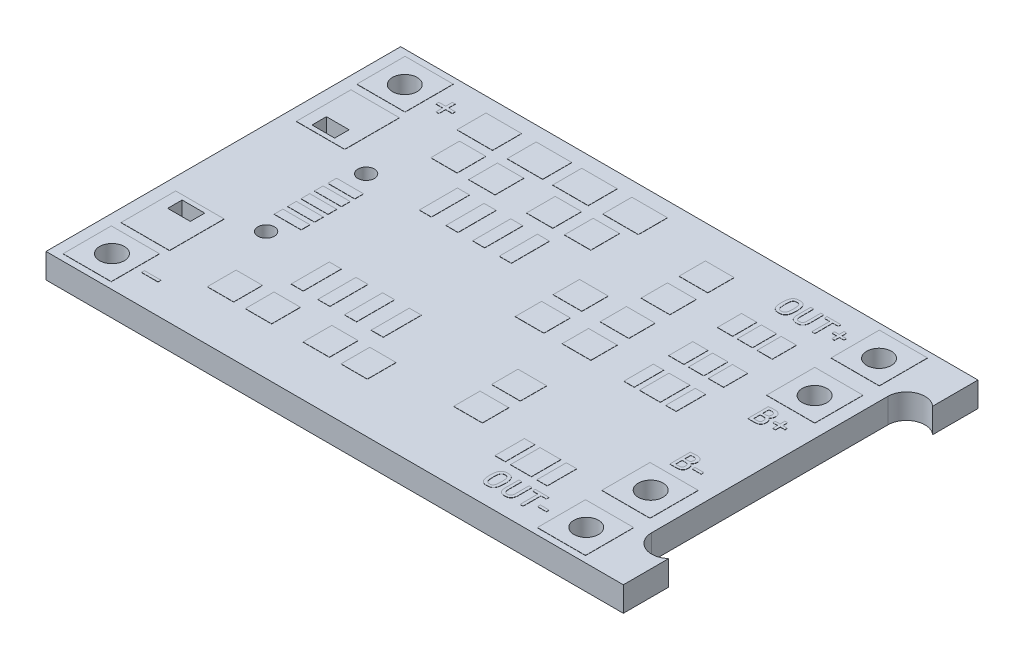
SolidWorks part; units mm, degrees
ref_plane "Front" through (0, 0, 0) normal (0, 0, 1) x (1, 0, 0)
ref_plane "Top" through (0, 0, 0) normal (0, 1, 0) x (1, 0, 0)
ref_plane "Right" through (0, 0, 0) normal (1, 0, 0) x (0, 0, -1)
sketch "Sketch1" plane through (0, 0, 0) normal (0, 1, 0) x (1, 0, 0)
  line L0 (0.5204, 8.2926) -> (0.5204, 5.9545) construction
  line L1 (0.5204, 5.9545) -> (2.8585, 5.9545) construction
  line L2 (2.8585, 5.9545) -> (2.8585, 8.2926) construction
  line L3 (2.8585, 8.2926) -> (0.5204, 8.2926) construction
  line L4 (23.5204, 8.2926) -> (23.5204, 5.9545) construction
  line L5 (23.5204, 5.9545) -> (25.8585, 5.9545) construction
  line L6 (25.8585, 5.9545) -> (25.8585, 8.2926) construction
  line L7 (25.8585, 8.2926) -> (23.5204, 8.2926) construction
  line L8 (0.5204, -8.2926) -> (0.5204, -5.9545) construction
  line L9 (0.5204, -5.9545) -> (2.8585, -5.9545) construction
  line L10 (2.8585, -5.9545) -> (2.8585, -8.2926) construction
  line L11 (2.8585, -8.2926) -> (0.5204, -8.2926) construction
  line L12 (23.5204, -8.2926) -> (23.5204, -5.9545) construction
  line L13 (23.5204, -5.9545) -> (25.8585, -5.9545) construction
  line L14 (25.8585, -5.9545) -> (25.8585, -8.2926) construction
  line L15 (25.8585, -8.2926) -> (23.5204, -8.2926) construction
  line L16 (23.5204, 5.165) -> (23.5204, 2.827) construction
  line L17 (23.5204, 2.827) -> (25.8585, 2.827) construction
  line L18 (25.8585, 2.827) -> (25.8585, 5.165) construction
  line L19 (25.8585, 5.165) -> (23.5204, 5.165) construction
  line L20 (23.5204, -5.165) -> (23.5204, -2.827) construction
  line L21 (23.5204, -2.827) -> (25.8585, -2.827) construction
  line L22 (25.8585, -2.827) -> (25.8585, -5.165) construction
  line L23 (25.8585, -5.165) -> (23.5204, -5.165) construction
  line L24 (26.5, 5.7292) -> (26.5, -5.7292)
  line L25 (4.865, 7.8748) -> (4.865, 6.4662) construction
  line L26 (4.865, 6.4662) -> (6.5892, 6.4662) construction
  line L27 (6.5892, 6.4662) -> (6.5892, 7.8748) construction
  line L28 (6.5892, 7.8748) -> (4.865, 7.8748) construction
  line L29 (7.2974, 7.8748) -> (7.2974, 6.4662) construction
  line L30 (7.2974, 6.4662) -> (9.0216, 6.4662) construction
  line L31 (9.0216, 6.4662) -> (9.0216, 7.8748) construction
  line L32 (9.0216, 7.8748) -> (7.2974, 7.8748) construction
  line L33 (9.5065, 7.8748) -> (9.5065, 6.4662) construction
  line L34 (9.5065, 6.4662) -> (11.2307, 6.4662) construction
  line L35 (11.2307, 6.4662) -> (11.2307, 7.8748) construction
  line L36 (11.2307, 7.8748) -> (9.5065, 7.8748) construction
  line L37 (11.9389, 7.8748) -> (11.9389, 6.4662) construction
  line L38 (11.9389, 6.4662) -> (13.6631, 6.4662) construction
  line L39 (13.6631, 6.4662) -> (13.6631, 7.8748) construction
  line L40 (13.6631, 7.8748) -> (11.9389, 7.8748) construction
  line L41 (5.4038, 6.0505) -> (5.4038, 4.6573) construction
  line L42 (5.4038, 4.6573) -> (6.6816, 4.6573) construction
  line L43 (6.6816, 4.6573) -> (6.6816, 6.0505) construction
  line L44 (6.6816, 6.0505) -> (5.4038, 6.0505) construction
  line L45 (7.2435, 6.0505) -> (7.2435, 4.6573) construction
  line L46 (7.2435, 4.6573) -> (8.5212, 4.6573) construction
  line L47 (8.5212, 4.6573) -> (8.5212, 6.0505) construction
  line L48 (8.5212, 6.0505) -> (7.2435, 6.0505) construction
  line L49 (10.0453, 6.0505) -> (10.0453, 4.6573) construction
  line L50 (10.0453, 4.6573) -> (11.3231, 4.6573) construction
  line L51 (11.3231, 4.6573) -> (11.3231, 6.0505) construction
  line L52 (11.3231, 6.0505) -> (10.0453, 6.0505) construction
  line L53 (11.885, 6.0505) -> (11.885, 4.6573) construction
  line L54 (11.885, 4.6573) -> (13.1627, 4.6573) construction
  line L55 (13.1627, 4.6573) -> (13.1627, 6.0505) construction
  line L56 (13.1627, 6.0505) -> (11.885, 6.0505) construction
  line L57 (5.4038, -4.7844) -> (5.4038, -6.1777) construction
  line L58 (5.4038, -6.1777) -> (6.6816, -6.1777) construction
  line L59 (6.6816, -6.1777) -> (6.6816, -4.7844) construction
  line L60 (6.6816, -4.7844) -> (5.4038, -4.7844) construction
  line L61 (7.2435, -4.7844) -> (7.2435, -6.1777) construction
  line L62 (7.2435, -6.1777) -> (8.5212, -6.1777) construction
  line L63 (8.5212, -6.1777) -> (8.5212, -4.7844) construction
  line L64 (8.5212, -4.7844) -> (7.2435, -4.7844) construction
  line L65 (10.0453, -4.7844) -> (10.0453, -6.1777) construction
  line L66 (10.0453, -6.1777) -> (11.3231, -6.1777) construction
  line L67 (11.3231, -6.1777) -> (11.3231, -4.7844) construction
  line L68 (11.3231, -4.7844) -> (10.0453, -4.7844) construction
  line L69 (11.885, -4.7844) -> (11.885, -6.1777) construction
  line L70 (11.885, -6.1777) -> (13.1627, -6.1777) construction
  line L71 (13.1627, -6.1777) -> (13.1627, -4.7844) construction
  line L72 (13.1627, -4.7844) -> (11.885, -4.7844) construction
  line L73 (0.6154, 5.5743) -> (0.6154, 2.9246) construction
  line L74 (0.6154, 2.9246) -> (2.9644, 2.9246) construction
  line L75 (2.9644, 2.9246) -> (2.9644, 5.5743) construction
  line L76 (2.9644, 5.5743) -> (0.6154, 5.5743) construction
  line L77 (0.6154, -5.5743) -> (0.6154, -2.9246) construction
  line L78 (0.6154, -2.9246) -> (2.9644, -2.9246) construction
  line L79 (2.9644, -2.9246) -> (2.9644, -5.5743) construction
  line L80 (2.9644, -5.5743) -> (0.6154, -5.5743) construction
  line L81 (17.7933, 6.9801) -> (16.4001, 6.9801) construction
  line L82 (16.4001, 6.9801) -> (16.4001, 5.7023) construction
  line L83 (16.4001, 5.7023) -> (17.7933, 5.7023) construction
  line L84 (17.7933, 5.7023) -> (17.7933, 6.9801) construction
  line L85 (17.7933, 5.1404) -> (16.4001, 5.1404) construction
  line L86 (16.4001, 5.1404) -> (16.4001, 3.8627) construction
  line L87 (16.4001, 3.8627) -> (17.7933, 3.8627) construction
  line L88 (17.7933, 3.8627) -> (17.7933, 5.1404) construction
  line L89 (17.7933, 3.1511) -> (16.4001, 3.1511) construction
  line L90 (16.4001, 3.1511) -> (16.4001, 1.8734) construction
  line L91 (16.4001, 1.8734) -> (17.7933, 1.8734) construction
  line L92 (17.7933, 1.8734) -> (17.7933, 3.1511) construction
  line L93 (17.7933, 1.3115) -> (16.4001, 1.3115) construction
  line L94 (16.4001, 1.3115) -> (16.4001, 0.0337) construction
  line L95 (16.4001, 0.0337) -> (17.7933, 0.0337) construction
  line L96 (17.7933, 0.0337) -> (17.7933, 1.3115) construction
  line L97 (17.7933, -2.1107) -> (16.4001, -2.1107) construction
  line L98 (16.4001, -2.1107) -> (16.4001, -3.3885) construction
  line L99 (16.4001, -3.3885) -> (17.7933, -3.3885) construction
  line L100 (17.7933, -3.3885) -> (17.7933, -2.1107) construction
  line L101 (17.7933, -3.9504) -> (16.4001, -3.9504) construction
  line L102 (16.4001, -3.9504) -> (16.4001, -5.2281) construction
  line L103 (16.4001, -5.2281) -> (17.7933, -5.2281) construction
  line L104 (17.7933, -5.2281) -> (17.7933, -3.9504) construction
  line L105 (15.5148, 3.1511) -> (14.1215, 3.1511) construction
  line L106 (14.1215, 3.1511) -> (14.1215, 1.8734) construction
  line L107 (14.1215, 1.8734) -> (15.5148, 1.8734) construction
  line L108 (15.5148, 1.8734) -> (15.5148, 3.1511) construction
  line L109 (15.5148, 1.3115) -> (14.1215, 1.3115) construction
  line L110 (14.1215, 1.3115) -> (14.1215, 0.0337) construction
  line L111 (14.1215, 0.0337) -> (15.5148, 0.0337) construction
  line L112 (15.5148, 0.0337) -> (15.5148, 1.3115) construction
  line L113 (19.4816, 5.6505) -> (19.4816, 4.4805) construction
  line L114 (19.4816, 4.4805) -> (20.2205, 4.4805) construction
  line L115 (20.2205, 4.4805) -> (20.2205, 5.6505) construction
  line L116 (20.2205, 5.6505) -> (19.4816, 5.6505) construction
  line L117 (20.4438, 5.6505) -> (20.4438, 4.4805) construction
  line L118 (20.4438, 4.4805) -> (21.1827, 4.4805) construction
  line L119 (21.1827, 4.4805) -> (21.1827, 5.6505) construction
  line L120 (21.1827, 5.6505) -> (20.4438, 5.6505) construction
  line L121 (21.4059, 5.6505) -> (21.4059, 4.4805) construction
  line L122 (21.4059, 4.4805) -> (22.1449, 4.4805) construction
  line L123 (22.1449, 4.4805) -> (22.1449, 5.6505) construction
  line L124 (22.1449, 5.6505) -> (21.4059, 5.6505) construction
  line L125 (19.4816, 3.2874) -> (19.4816, 2.1174) construction
  line L126 (19.4816, 2.1174) -> (20.2205, 2.1174) construction
  line L127 (20.2205, 2.1174) -> (20.2205, 3.2874) construction
  line L128 (20.2205, 3.2874) -> (19.4816, 3.2874) construction
  line L129 (20.4438, 3.2874) -> (20.4438, 2.1174) construction
  line L130 (20.4438, 2.1174) -> (21.1827, 2.1174) construction
  line L131 (21.1827, 2.1174) -> (21.1827, 3.2874) construction
  line L132 (21.1827, 3.2874) -> (20.4438, 3.2874) construction
  line L133 (21.4059, 3.2874) -> (21.4059, 2.1174) construction
  line L134 (21.4059, 2.1174) -> (22.1449, 2.1174) construction
  line L135 (22.1449, 2.1174) -> (22.1449, 3.2874) construction
  line L136 (22.1449, 3.2874) -> (21.4059, 3.2874) construction
  line L137 (5.2898, 1.0876) -> (5.2898, 1.5124) construction
  line L138 (5.2898, 1.5124) -> (3.9782, 1.5124) construction
  line L139 (3.9782, 1.5124) -> (3.9782, 1.0876) construction
  line L140 (3.9782, 1.0876) -> (5.2898, 1.0876) construction
  line L141 (5.2898, 0.4376) -> (5.2898, 0.8624) construction
  line L142 (5.2898, 0.8624) -> (3.9782, 0.8624) construction
  line L143 (3.9782, 0.8624) -> (3.9782, 0.4376) construction
  line L144 (3.9782, 0.4376) -> (5.2898, 0.4376) construction
  line L145 (5.2898, -0.2124) -> (5.2898, 0.2124) construction
  line L146 (5.2898, 0.2124) -> (3.9782, 0.2124) construction
  line L147 (3.9782, 0.2124) -> (3.9782, -0.2124) construction
  line L148 (3.9782, -0.2124) -> (5.2898, -0.2124) construction
  line L149 (5.2898, -0.8624) -> (5.2898, -0.4376) construction
  line L150 (5.2898, -0.4376) -> (3.9782, -0.4376) construction
  line L151 (3.9782, -0.4376) -> (3.9782, -0.8624) construction
  line L152 (3.9782, -0.8624) -> (5.2898, -0.8624) construction
  line L153 (5.2898, -1.5124) -> (5.2898, -1.0876) construction
  line L154 (5.2898, -1.0876) -> (3.9782, -1.0876) construction
  line L155 (3.9782, -1.0876) -> (3.9782, -1.5124) construction
  line L156 (3.9782, -1.5124) -> (5.2898, -1.5124) construction
  line L157 (11.787, 4.0316) -> (11.787, 2.1824) construction
  line L158 (11.787, 2.1824) -> (11.2007, 2.1824) construction
  line L159 (11.2007, 2.1824) -> (11.2007, 4.0316) construction
  line L160 (11.2007, 4.0316) -> (11.787, 4.0316) construction
  line L161 (10.4941, 4.0316) -> (10.4941, 2.1824) construction
  line L162 (10.4941, 2.1824) -> (9.9077, 2.1824) construction
  line L163 (9.9077, 2.1824) -> (9.9077, 4.0316) construction
  line L164 (9.9077, 4.0316) -> (10.4941, 4.0316) construction
  line L165 (9.2011, 4.0316) -> (9.2011, 2.1824) construction
  line L166 (9.2011, 2.1824) -> (8.6148, 2.1824) construction
  line L167 (8.6148, 2.1824) -> (8.6148, 4.0316) construction
  line L168 (8.6148, 4.0316) -> (9.2011, 4.0316) construction
  line L169 (7.9082, 4.0316) -> (7.9082, 2.1824) construction
  line L170 (7.9082, 2.1824) -> (7.3219, 2.1824) construction
  line L171 (7.3219, 2.1824) -> (7.3219, 4.0316) construction
  line L172 (7.3219, 4.0316) -> (7.9082, 4.0316) construction
  line L173 (7.9082, -4.0316) -> (7.9082, -2.1824) construction
  line L174 (7.9082, -2.1824) -> (7.3219, -2.1824) construction
  line L175 (7.3219, -2.1824) -> (7.3219, -4.0316) construction
  line L176 (7.3219, -4.0316) -> (7.9082, -4.0316) construction
  line L177 (9.2011, -4.0316) -> (9.2011, -2.1824) construction
  line L178 (9.2011, -2.1824) -> (8.6148, -2.1824) construction
  line L179 (8.6148, -2.1824) -> (8.6148, -4.0316) construction
  line L180 (8.6148, -4.0316) -> (9.2011, -4.0316) construction
  line L181 (10.4941, -4.0316) -> (10.4941, -2.1824) construction
  line L182 (10.4941, -2.1824) -> (9.9077, -2.1824) construction
  line L183 (9.9077, -2.1824) -> (9.9077, -4.0316) construction
  line L184 (9.9077, -4.0316) -> (10.4941, -4.0316) construction
  line L185 (11.787, -4.0316) -> (11.787, -2.1824) construction
  line L186 (11.787, -2.1824) -> (11.2007, -2.1824) construction
  line L187 (11.2007, -2.1824) -> (11.2007, -4.0316) construction
  line L188 (11.2007, -4.0316) -> (11.787, -4.0316) construction
  line L189 (19.47, 1.3863) -> (19.47, -0.0449) construction
  line L190 (19.47, -0.0449) -> (19.9752, -0.0449) construction
  line L191 (19.9752, -0.0449) -> (19.9752, 1.3863) construction
  line L192 (19.9752, 1.3863) -> (19.47, 1.3863) construction
  line L193 (21.5026, 1.3863) -> (21.5026, -0.0449) construction
  line L194 (21.5026, -0.0449) -> (22.0078, -0.0449) construction
  line L195 (22.0078, -0.0449) -> (22.0078, 1.3863) construction
  line L196 (22.0078, 1.3863) -> (21.5026, 1.3863) construction
  line L197 (20.2278, 1.3863) -> (20.2278, -0.0449) construction
  line L198 (20.2278, -0.0449) -> (21.238, -0.0449) construction
  line L199 (21.238, -0.0449) -> (21.238, 1.3863) construction
  line L200 (21.238, 1.3863) -> (20.2278, 1.3863) construction
  line L201 (19.47, -4.8678) -> (19.47, -6.299) construction
  line L202 (19.47, -6.299) -> (19.9752, -6.299) construction
  line L203 (19.9752, -6.299) -> (19.9752, -4.8678) construction
  line L204 (19.9752, -4.8678) -> (19.47, -4.8678) construction
  line L205 (20.2278, -4.8678) -> (20.2278, -6.299) construction
  line L206 (20.2278, -6.299) -> (21.238, -6.299) construction
  line L207 (21.238, -6.299) -> (21.238, -4.8678) construction
  line L208 (21.238, -4.8678) -> (20.2278, -4.8678) construction
  line L209 (21.5026, -4.8678) -> (21.5026, -6.299) construction
  line L210 (21.5026, -6.299) -> (22.0078, -6.299) construction
  line L211 (22.0078, -6.299) -> (22.0078, -4.8678) construction
  line L212 (22.0078, -4.8678) -> (21.5026, -4.8678) construction
  line L213 (28, 8.6) -> (0, 8.6)
  line L214 (0, 8.6) -> (0, -8.6)
  line L215 (0, -8.6) -> (28, -8.6)
  line L216 (28, -8.6) -> (28, -6.4)
  line L217 (28, 6.4) -> (28, 8.6)
  line L218 (0, 0) -> (26.5, 0) construction
  line L219 (2.25, -3.15) -> (2.25, -3.85)
  line L220 (1.15, 3.15) -> (2.25, 3.15)
  line L221 (1.15, 3.15) -> (1.15, 3.85)
  line L222 (1.15, 3.85) -> (2.25, 3.85)
  line L223 (2.25, 3.15) -> (2.25, 3.85)
  line L224 (1.15, -3.85) -> (2.25, -3.85)
  line L225 (1.15, -3.15) -> (1.15, -3.85)
  line L226 (1.15, -3.15) -> (2.25, -3.15)
  circle A0 centre (24.7, 7.1) radius 0.6
  circle A1 centre (1.7, 7.1) radius 0.6
  circle A2 centre (24.7, -7.1) radius 0.6
  circle A3 centre (1.7, -7.1) radius 0.6
  circle A4 centre (24.7, 3.9747) radius 0.6
  circle A5 centre (24.7, -3.975) radius 0.6
  arc A6 (28, 6.4) -> (26.5, 5.7292) centre (27.4, 5.7292) ccw
  arc A7 (26.5, -5.7292) -> (28, -6.4) centre (27.4, -5.7292) ccw
  circle A8 centre (4.5, 2.425) radius 0.4
  circle A9 centre (4.5, -2.425) radius 0.4
  point P245 (1.7, 3.15)
  dimension "D5" = 0.9
  dimension "D6" = 1.2
  dimension "D8" = 23
  dimension "D10" = 14.2
  dimension "D11" = 3.125
  dimension "D12" = 3.1253
  dimension "D13" = 0.8
  dimension "D1" = 28
  dimension "D2" = 17.1999
  dimension "D3" = 1.5
  dimension "D4" = 12.8
  dimension "D7" = 1.7
  dimension "D9" = 1.5
  dimension "D14" = 2.425
  dimension "D15" = 4.5
  dimension "D16" = 1.1
  dimension "D17" = 0.7
  dimension "D18" = 3.15
extrude "PCB" add sketch "Sketch1" along normal blind 1.2
sketch "Sketch2" plane through (0, 1.2, 0) normal (0, 1, 0) x (1, 0, 0)
  line L0 (3.6016, 7.1809) -> (3.6016, 7.5098)
  line L1 (0.5204, 8.2926) -> (2.8585, 8.2926)
  line L2 (0.5204, 8.2926) -> (0.5204, 5.9545)
  line L3 (0.5204, 5.9545) -> (2.8585, 5.9545)
  line L4 (2.8585, 8.2926) -> (2.8585, 5.9545)
  line L5 (0.6154, 5.5743) -> (2.9644, 5.5743)
  line L6 (0.6154, 5.5743) -> (0.6154, 2.9246)
  line L7 (0.6154, 2.9246) -> (2.9644, 2.9246)
  line L8 (2.9644, 5.5743) -> (2.9644, 2.9246)
  line L9 (0.6154, -2.9246) -> (2.9644, -2.9246)
  line L10 (0.6154, -2.9246) -> (0.6154, -5.5743)
  line L11 (0.6154, -5.5743) -> (2.9644, -5.5743)
  line L12 (2.9644, -2.9246) -> (2.9644, -5.5743)
  line L13 (0.5204, -5.9545) -> (2.8585, -5.9545)
  line L14 (0.5204, -5.9545) -> (0.5204, -8.2926)
  line L15 (0.5204, -8.2926) -> (2.8585, -8.2926)
  line L16 (2.8585, -5.9545) -> (2.8585, -8.2926)
  line L17 (4.865, 7.8748) -> (6.5892, 7.8748)
  line L18 (4.865, 7.8748) -> (4.865, 6.4662)
  line L19 (4.865, 6.4662) -> (6.5892, 6.4662)
  line L20 (6.5892, 7.8748) -> (6.5892, 6.4662)
  line L21 (7.2974, 7.8748) -> (9.0216, 7.8748)
  line L22 (7.2974, 7.8748) -> (7.2974, 6.4662)
  line L23 (7.2974, 6.4662) -> (9.0216, 6.4662)
  line L24 (9.0216, 7.8748) -> (9.0216, 6.4662)
  line L25 (9.5065, 7.8748) -> (11.2307, 7.8748)
  line L26 (9.5065, 7.8748) -> (9.5065, 6.4662)
  line L27 (9.5065, 6.4662) -> (11.2307, 6.4662)
  line L28 (11.2307, 7.8748) -> (11.2307, 6.4662)
  line L29 (11.9389, 7.8748) -> (13.6631, 7.8748)
  line L30 (11.9389, 7.8748) -> (11.9389, 6.4662)
  line L31 (11.9389, 6.4662) -> (13.6631, 6.4662)
  line L32 (13.6631, 7.8748) -> (13.6631, 6.4662)
  line L33 (5.4038, 6.0505) -> (6.6816, 6.0505)
  line L34 (5.4038, 6.0505) -> (5.4038, 4.6573)
  line L35 (5.4038, 4.6573) -> (6.6816, 4.6573)
  line L36 (6.6816, 6.0505) -> (6.6816, 4.6573)
  line L37 (7.2435, 6.0505) -> (8.5212, 6.0505)
  line L38 (7.2435, 6.0505) -> (7.2435, 4.6573)
  line L39 (7.2435, 4.6573) -> (8.5212, 4.6573)
  line L40 (8.5212, 6.0505) -> (8.5212, 4.6573)
  line L41 (10.0453, 6.0505) -> (11.3231, 6.0505)
  line L42 (10.0453, 6.0505) -> (10.0453, 4.6573)
  line L43 (10.0453, 4.6573) -> (11.3231, 4.6573)
  line L44 (11.3231, 6.0505) -> (11.3231, 4.6573)
  line L45 (11.885, 6.0505) -> (13.1627, 6.0505)
  line L46 (11.885, 6.0505) -> (11.885, 4.6573)
  line L47 (11.885, 4.6573) -> (13.1627, 4.6573)
  line L48 (13.1627, 6.0505) -> (13.1627, 4.6573)
  line L49 (7.3219, 4.0316) -> (7.9082, 4.0316)
  line L50 (7.3219, 4.0316) -> (7.3219, 2.1824)
  line L51 (7.3219, 2.1824) -> (7.9082, 2.1824)
  line L52 (7.9082, 4.0316) -> (7.9082, 2.1824)
  line L53 (8.6148, 4.0316) -> (9.2011, 4.0316)
  line L54 (8.6148, 4.0316) -> (8.6148, 2.1824)
  line L55 (8.6148, 2.1824) -> (9.2011, 2.1824)
  line L56 (9.2011, 4.0316) -> (9.2011, 2.1824)
  line L57 (9.9077, 4.0316) -> (10.4941, 4.0316)
  line L58 (9.9077, 4.0316) -> (9.9077, 2.1824)
  line L59 (9.9077, 2.1824) -> (10.4941, 2.1824)
  line L60 (10.4941, 4.0316) -> (10.4941, 2.1824)
  line L61 (11.2007, 4.0316) -> (11.787, 4.0316)
  line L62 (11.2007, 4.0316) -> (11.2007, 2.1824)
  line L63 (11.2007, 2.1824) -> (11.787, 2.1824)
  line L64 (11.787, 4.0316) -> (11.787, 2.1824)
  line L65 (16.4001, 6.9801) -> (17.7933, 6.9801)
  line L66 (16.4001, 6.9801) -> (16.4001, 5.7023)
  line L67 (16.4001, 5.7023) -> (17.7933, 5.7023)
  line L68 (17.7933, 6.9801) -> (17.7933, 5.7023)
  line L69 (16.4001, 5.1404) -> (17.7933, 5.1404)
  line L70 (16.4001, 5.1404) -> (16.4001, 3.8627)
  line L71 (16.4001, 3.8627) -> (17.7933, 3.8627)
  line L72 (17.7933, 5.1404) -> (17.7933, 3.8627)
  line L73 (16.4001, 3.1511) -> (17.7933, 3.1511)
  line L74 (16.4001, 3.1511) -> (16.4001, 1.8734)
  line L75 (16.4001, 1.8734) -> (17.7933, 1.8734)
  line L76 (17.7933, 3.1511) -> (17.7933, 1.8734)
  line L77 (16.4001, 1.3115) -> (17.7933, 1.3115)
  line L78 (16.4001, 1.3115) -> (16.4001, 0.0337)
  line L79 (16.4001, 0.0337) -> (17.7933, 0.0337)
  line L80 (17.7933, 1.3115) -> (17.7933, 0.0337)
  line L81 (14.1215, 3.1511) -> (15.5148, 3.1511)
  line L82 (14.1215, 3.1511) -> (14.1215, 1.8734)
  line L83 (14.1215, 1.8734) -> (15.5148, 1.8734)
  line L84 (15.5148, 3.1511) -> (15.5148, 1.8734)
  line L85 (14.1215, 1.3115) -> (15.5148, 1.3115)
  line L86 (14.1215, 1.3115) -> (14.1215, 0.0337)
  line L87 (14.1215, 0.0337) -> (15.5148, 0.0337)
  line L88 (15.5148, 1.3115) -> (15.5148, 0.0337)
  line L89 (3.9782, 1.5124) -> (5.2898, 1.5124)
  line L90 (3.9782, 1.5124) -> (3.9782, 1.0876)
  line L91 (3.9782, 1.0876) -> (5.2898, 1.0876)
  line L92 (5.2898, 1.5124) -> (5.2898, 1.0876)
  line L93 (3.9782, 0.8624) -> (5.2898, 0.8624)
  line L94 (3.9782, 0.8624) -> (3.9782, 0.4376)
  line L95 (3.9782, 0.4376) -> (5.2898, 0.4376)
  line L96 (5.2898, 0.8624) -> (5.2898, 0.4376)
  line L97 (3.9782, 0.2124) -> (5.2898, 0.2124)
  line L98 (3.9782, 0.2124) -> (3.9782, -0.2124)
  line L99 (3.9782, -0.2124) -> (5.2898, -0.2124)
  line L100 (5.2898, 0.2124) -> (5.2898, -0.2124)
  line L101 (3.9782, -0.4376) -> (5.2898, -0.4376)
  line L102 (3.9782, -0.4376) -> (3.9782, -0.8624)
  line L103 (3.9782, -0.8624) -> (5.2898, -0.8624)
  line L104 (5.2898, -0.4376) -> (5.2898, -0.8624)
  line L105 (3.9782, -1.0876) -> (5.2898, -1.0876)
  line L106 (3.9782, -1.0876) -> (3.9782, -1.5124)
  line L107 (3.9782, -1.5124) -> (5.2898, -1.5124)
  line L108 (5.2898, -1.0876) -> (5.2898, -1.5124)
  line L109 (7.3219, -2.1824) -> (7.9082, -2.1824)
  line L110 (7.3219, -2.1824) -> (7.3219, -4.0316)
  line L111 (7.3219, -4.0316) -> (7.9082, -4.0316)
  line L112 (7.9082, -2.1824) -> (7.9082, -4.0316)
  line L113 (8.6148, -2.1824) -> (9.2011, -2.1824)
  line L114 (8.6148, -2.1824) -> (8.6148, -4.0316)
  line L115 (8.6148, -4.0316) -> (9.2011, -4.0316)
  line L116 (9.2011, -2.1824) -> (9.2011, -4.0316)
  line L117 (9.9077, -2.1824) -> (10.4941, -2.1824)
  line L118 (9.9077, -2.1824) -> (9.9077, -4.0316)
  line L119 (9.9077, -4.0316) -> (10.4941, -4.0316)
  line L120 (10.4941, -2.1824) -> (10.4941, -4.0316)
  line L121 (11.2007, -2.1824) -> (11.787, -2.1824)
  line L122 (11.2007, -2.1824) -> (11.2007, -4.0316)
  line L123 (11.2007, -4.0316) -> (11.787, -4.0316)
  line L124 (11.787, -2.1824) -> (11.787, -4.0316)
  line L125 (5.4038, -4.7844) -> (6.6816, -4.7844)
  line L126 (5.4038, -4.7844) -> (5.4038, -6.1777)
  line L127 (5.4038, -6.1777) -> (6.6816, -6.1777)
  line L128 (6.6816, -4.7844) -> (6.6816, -6.1777)
  line L129 (7.2435, -4.7844) -> (8.5212, -4.7844)
  line L130 (7.2435, -4.7844) -> (7.2435, -6.1777)
  line L131 (7.2435, -6.1777) -> (8.5212, -6.1777)
  line L132 (8.5212, -4.7844) -> (8.5212, -6.1777)
  line L133 (10.0453, -4.7844) -> (11.3231, -4.7844)
  line L134 (10.0453, -4.7844) -> (10.0453, -6.1777)
  line L135 (10.0453, -6.1777) -> (11.3231, -6.1777)
  line L136 (11.3231, -4.7844) -> (11.3231, -6.1777)
  line L137 (11.885, -4.7844) -> (13.1627, -4.7844)
  line L138 (11.885, -4.7844) -> (11.885, -6.1777)
  line L139 (11.885, -6.1777) -> (13.1627, -6.1777)
  line L140 (13.1627, -4.7844) -> (13.1627, -6.1777)
  line L141 (16.4001, -2.1107) -> (17.7933, -2.1107)
  line L142 (16.4001, -2.1107) -> (16.4001, -3.3885)
  line L143 (16.4001, -3.3885) -> (17.7933, -3.3885)
  line L144 (17.7933, -2.1107) -> (17.7933, -3.3885)
  line L145 (16.4001, -3.9504) -> (17.7933, -3.9504)
  line L146 (16.4001, -3.9504) -> (16.4001, -5.2281)
  line L147 (16.4001, -5.2281) -> (17.7933, -5.2281)
  line L148 (17.7933, -3.9504) -> (17.7933, -5.2281)
  line L149 (19.4816, 5.6505) -> (20.2205, 5.6505)
  line L150 (19.4816, 5.6505) -> (19.4816, 4.4805)
  line L151 (19.4816, 4.4805) -> (20.2205, 4.4805)
  line L152 (20.2205, 5.6505) -> (20.2205, 4.4805)
  line L153 (20.4438, 5.6505) -> (21.1827, 5.6505)
  line L154 (20.4438, 5.6505) -> (20.4438, 4.4805)
  line L155 (20.4438, 4.4805) -> (21.1827, 4.4805)
  line L156 (21.1827, 5.6505) -> (21.1827, 4.4805)
  line L157 (21.4059, 5.6505) -> (22.1449, 5.6505)
  line L158 (21.4059, 5.6505) -> (21.4059, 4.4805)
  line L159 (21.4059, 4.4805) -> (22.1449, 4.4805)
  line L160 (22.1449, 5.6505) -> (22.1449, 4.4805)
  line L161 (19.4816, 3.2874) -> (20.2205, 3.2874)
  line L162 (19.4816, 3.2874) -> (19.4816, 2.1174)
  line L163 (19.4816, 2.1174) -> (20.2205, 2.1174)
  line L164 (20.2205, 3.2874) -> (20.2205, 2.1174)
  line L165 (20.4438, 3.2874) -> (21.1827, 3.2874)
  line L166 (20.4438, 3.2874) -> (20.4438, 2.1174)
  line L167 (20.4438, 2.1174) -> (21.1827, 2.1174)
  line L168 (21.1827, 3.2874) -> (21.1827, 2.1174)
  line L169 (21.4059, 3.2874) -> (22.1449, 3.2874)
  line L170 (21.4059, 3.2874) -> (21.4059, 2.1174)
  line L171 (21.4059, 2.1174) -> (22.1449, 2.1174)
  line L172 (22.1449, 3.2874) -> (22.1449, 2.1174)
  line L173 (19.47, 1.3863) -> (19.9752, 1.3863)
  line L174 (19.47, 1.3863) -> (19.47, -0.0449)
  line L175 (19.47, -0.0449) -> (19.9752, -0.0449)
  line L176 (19.9752, 1.3863) -> (19.9752, -0.0449)
  line L177 (20.2278, 1.3863) -> (21.238, 1.3863)
  line L178 (20.2278, 1.3863) -> (20.2278, -0.0449)
  line L179 (20.2278, -0.0449) -> (21.238, -0.0449)
  line L180 (21.238, 1.3863) -> (21.238, -0.0449)
  line L181 (21.5026, 1.3863) -> (22.0078, 1.3863)
  line L182 (21.5026, 1.3863) -> (21.5026, -0.0449)
  line L183 (21.5026, -0.0449) -> (22.0078, -0.0449)
  line L184 (22.0078, 1.3863) -> (22.0078, -0.0449)
  line L185 (19.47, -4.8678) -> (19.9752, -4.8678)
  line L186 (19.47, -4.8678) -> (19.47, -6.299)
  line L187 (19.47, -6.299) -> (19.9752, -6.299)
  line L188 (19.9752, -4.8678) -> (19.9752, -6.299)
  line L189 (20.2278, -4.8678) -> (21.238, -4.8678)
  line L190 (20.2278, -4.8678) -> (20.2278, -6.299)
  line L191 (20.2278, -6.299) -> (21.238, -6.299)
  line L192 (21.238, -4.8678) -> (21.238, -6.299)
  line L193 (21.5026, -4.8678) -> (22.0078, -4.8678)
  line L194 (21.5026, -4.8678) -> (21.5026, -6.299)
  line L195 (21.5026, -6.299) -> (22.0078, -6.299)
  line L196 (22.0078, -4.8678) -> (22.0078, -6.299)
  line L197 (23.5204, -5.9545) -> (25.8585, -5.9545)
  line L198 (23.5204, -5.9545) -> (23.5204, -8.2926)
  line L199 (23.5204, -8.2926) -> (25.8585, -8.2926)
  line L200 (25.8585, -5.9545) -> (25.8585, -8.2926)
  line L201 (23.5204, -2.827) -> (25.8585, -2.827)
  line L202 (23.5204, -2.827) -> (23.5204, -5.165)
  line L203 (23.5204, -5.165) -> (25.8585, -5.165)
  line L204 (25.8585, -2.827) -> (25.8585, -5.165)
  line L205 (23.5204, 5.165) -> (25.8585, 5.165)
  line L206 (23.5204, 5.165) -> (23.5204, 2.827)
  line L207 (23.5204, 2.827) -> (25.8585, 2.827)
  line L208 (25.8585, 5.165) -> (25.8585, 2.827)
  line L209 (23.5204, 8.2926) -> (25.8585, 8.2926)
  line L210 (23.5204, 8.2926) -> (23.5204, 5.9545)
  line L211 (23.5204, 5.9545) -> (25.8585, 5.9545)
  line L212 (25.8585, 8.2926) -> (25.8585, 5.9545)
  line L213 (3.2728, 7.0386) -> (3.6016, 7.0386)
  line L214 (3.2016, -7.1711) -> (3.2016, -7.0288)
  line L215 (3.2728, 7.1809) -> (3.6016, 7.1809)
  line L216 (4.0016, -7.1711) -> (4.0016, -7.0288)
  line L217 (4.865, 7.1705) -> (9.0216, 7.1705) construction
  line L218 (9.5065, 7.1705) -> (13.6631, 7.1705) construction
  line L219 (3.6016, 6.7098) -> (3.7439, 6.7098)
  line L220 (3.6016, 6.7098) -> (3.6016, 7.0386)
  line L221 (3.6016, 7.5098) -> (3.7439, 7.5098)
  line L222 (3.7439, 6.7098) -> (3.7439, 7.0386)
  line L223 (5.4038, 5.3539) -> (8.5212, 5.3539) construction
  line L224 (10.0453, 5.3539) -> (13.1627, 5.3539) construction
  line L225 (7.3219, 0) -> (11.787, 0) construction
  line L226 (3.7439, 7.1809) -> (4.0728, 7.1809)
  line L227 (3.7439, 7.1809) -> (3.7439, 7.5098)
  line L228 (7.3219, 4.0316) -> (11.787, 4.0316) construction
  line L229 (3.7439, 7.0386) -> (4.0728, 7.0386)
  line L230 (7.3219, 4.0316) -> (7.3219, -4.0316) construction
  line L231 (7.3219, -4.0316) -> (11.787, -4.0316) construction
  line L232 (11.787, 4.0316) -> (11.787, -4.0316) construction
  line L233 (3.2016, -7.0288) -> (4.0016, -7.0288)
  line L234 (3.2728, 7.1809) -> (3.2728, 7.0386)
  line L235 (3.2016, -7.1711) -> (4.0016, -7.1711)
  line L236 (4.0728, 7.1809) -> (4.0728, 7.0386)
  line L237 (9.5544, 4.0316) -> (9.5544, -4.0316) construction
  line L238 (5.4038, -5.481) -> (8.5212, -5.481) construction
  line L239 (20.7329, 1.3863) -> (20.7329, -6.299) construction
  line L240 (10.0453, -5.481) -> (13.1627, -5.481) construction
  line L241 (17.0967, -5.2281) -> (17.0967, -2.1107) construction
  line L242 (17.0967, 0.0337) -> (17.0967, 3.1511) construction
  line L243 (20.8132, 5.6505) -> (20.8132, 2.1174) construction
  line L244 (17.0967, 3.8627) -> (17.0967, 6.9801) construction
  line L245 (6.9433, 7.1705) -> (6.9433, 6.4662) construction
  line L246 (14.8181, 3.1511) -> (14.8181, 0.0337) construction
  line L247 (11.5848, 7.1705) -> (11.5848, 6.4662) construction
  line L248 (6.9625, 5.3539) -> (6.9625, 4.6573) construction
  line L249 (11.604, 5.3539) -> (11.604, 4.6573) construction
  line L250 (6.9625, -5.481) -> (6.9625, -6.1777) construction
  line L251 (11.604, -5.481) -> (11.604, -6.1777) construction
  line L252 (14.8181, 1.5924) -> (17.0967, 1.5924) construction
  line L253 (20.7329, -2.4563) -> (22.0078, -2.4563) construction
  line L254 (17.0967, -3.6694) -> (17.7933, -3.6694) construction
  line L255 (17.0967, 5.4214) -> (17.7933, 5.4214) construction
  line L256 (20.8132, 3.8839) -> (22.1449, 3.8839) construction
  line L257 (2.25, 3.15) -> (2.25, 3.85) construction
  line L258 (2.25, 3.85) -> (1.15, 3.85) construction
  line L259 (1.15, 3.85) -> (1.15, 3.15) construction
  line L260 (1.15, 3.15) -> (2.25, 3.15) construction
  line L261 (2.25, 3.15) -> (2.25, 3.85)
  line L262 (2.25, 3.85) -> (1.15, 3.85)
  line L263 (1.15, 3.85) -> (1.15, 3.15)
  line L264 (1.15, 3.15) -> (2.25, 3.15)
  line L265 (2.25, -3.85) -> (2.25, -3.15) construction
  line L266 (2.25, -3.15) -> (1.15, -3.15) construction
  line L267 (1.15, -3.15) -> (1.15, -3.85) construction
  line L268 (1.15, -3.85) -> (2.25, -3.85) construction
  line L269 (2.25, -3.85) -> (2.25, -3.15)
  line L270 (2.25, -3.15) -> (1.15, -3.15)
  line L271 (1.15, -3.15) -> (1.15, -3.85)
  line L272 (1.15, -3.85) -> (2.25, -3.85)
  circle A0 centre (24.7, 7.1) radius 0.6 construction
  circle A1 centre (24.7, 3.9747) radius 0.6 construction
  circle A2 centre (24.7, -3.975) radius 0.6 construction
  circle A3 centre (24.7, -7.1) radius 0.6 construction
  circle A4 centre (1.7, -7.1) radius 0.6 construction
  circle A5 centre (1.7, 7.1) radius 0.6 construction
  circle A6 centre (24.7, 7.1) radius 0.6
  circle A7 centre (24.7, 3.9747) radius 0.6
  circle A8 centre (24.7, -3.975) radius 0.6
  circle A9 centre (24.7, -7.1) radius 0.6
  circle A10 centre (1.7, -7.1) radius 0.6
  circle A11 centre (1.7, 7.1) radius 0.6
extrude "Pads - Component Side" add sketch "Sketch2" along normal blind 0.01
sketch "Sketch3" plane through (0, 0, 0) normal (0, -1, 0) x (1, 0, 0)
  line L1 (0.5204, 8.2926) -> (2.8585, 8.2926)
  line L2 (0.5204, 8.2926) -> (0.5204, 5.9545)
  line L3 (0.5204, 5.9545) -> (2.8585, 5.9545)
  line L4 (2.8585, 8.2926) -> (2.8585, 5.9545)
  line L5 (0.5204, -5.9545) -> (2.8585, -5.9545)
  line L6 (0.5204, -5.9545) -> (0.5204, -8.2926)
  line L7 (0.5204, -8.2926) -> (2.8585, -8.2926)
  line L8 (2.8585, -5.9545) -> (2.8585, -8.2926)
  line L9 (23.5204, 8.2926) -> (25.8585, 8.2926)
  line L10 (23.5204, 8.2926) -> (23.5204, 5.9545)
  line L11 (23.5204, 5.9545) -> (25.8585, 5.9545)
  line L12 (25.8585, 8.2926) -> (25.8585, 5.9545)
  line L13 (23.5204, -5.9545) -> (25.8585, -5.9545)
  line L14 (23.5204, -5.9545) -> (23.5204, -8.2926)
  line L15 (23.5204, -8.2926) -> (25.8585, -8.2926)
  line L16 (25.8585, -5.9545) -> (25.8585, -8.2926)
  line L17 (23.5204, -2.827) -> (25.8585, -2.827)
  line L18 (23.5204, -2.827) -> (23.5204, -5.165)
  line L19 (23.5204, -5.165) -> (25.8585, -5.165)
  line L20 (25.8585, -2.827) -> (25.8585, -5.165)
  line L21 (23.5204, 5.165) -> (25.8585, 5.165)
  line L22 (23.5204, 5.165) -> (23.5204, 2.827)
  line L23 (23.5204, 2.827) -> (25.8585, 2.827)
  line L24 (25.8585, 5.165) -> (25.8585, 2.827)
  circle A0 centre (24.7, 7.1) radius 0.6 construction
  circle A1 centre (24.7, 3.975) radius 0.6 construction
  circle A2 centre (24.7, -3.9747) radius 0.6 construction
  circle A3 centre (24.7, -7.1) radius 0.6 construction
  circle A4 centre (1.7, -7.1) radius 0.6 construction
  circle A5 centre (1.7, 7.1) radius 0.6 construction
  circle A6 centre (24.7, 7.1) radius 0.6
  circle A7 centre (24.7, 3.975) radius 0.6
  circle A8 centre (24.7, -3.9747) radius 0.6
  circle A9 centre (24.7, -7.1) radius 0.6
  circle A10 centre (1.7, -7.1) radius 0.6
  circle A11 centre (1.7, 7.1) radius 0.6
extrude "Pads - Solder side" add sketch "Sketch3" along normal blind 0.01
sketch "Sketch4" plane through (0, 1.2, 0) normal (0, 1, 0) x (1, 0, 0)
  line L0 (19.5093, 6.5911) -> (23.1791, 6.5911) construction
  text T0 "OUT+" font "HP Simplified" height 1
extrude "Legend - Out+" add sketch "Sketch4" along normal blind 0.01
sketch "Sketch5" plane through (0, 1.2, 0) normal (0, 1, 0) x (1, 0, 0)
  line L0 (23.1414, -7.739) -> (18.9163, -7.739) construction
  text T0 "OUT-" font "HP Simplified" height 1
extrude "Legend - Out-" add sketch "Sketch5" along normal blind 0.01
sketch "Sketch6" plane through (0, 1.2, 0) normal (0, 1, 0) x (1, 0, 0)
  line L0 (23.5862, 1.396) -> (25.8593, 1.396) construction
  text T0 "B+" font "HP Simplified" height 1
extrude "Legend - B+" add sketch "Sketch6" along normal blind 0.01
sketch "Sketch7" plane through (0, 1.2, 0) normal (0, 1, 0) x (1, 0, 0)
  line L0 (23.5367, -2.409) -> (25.7358, -2.409) construction
  text T0 "B-" font "HP Simplified" height 1
extrude "Legend - B-" add sketch "Sketch7" along normal blind 0.01
